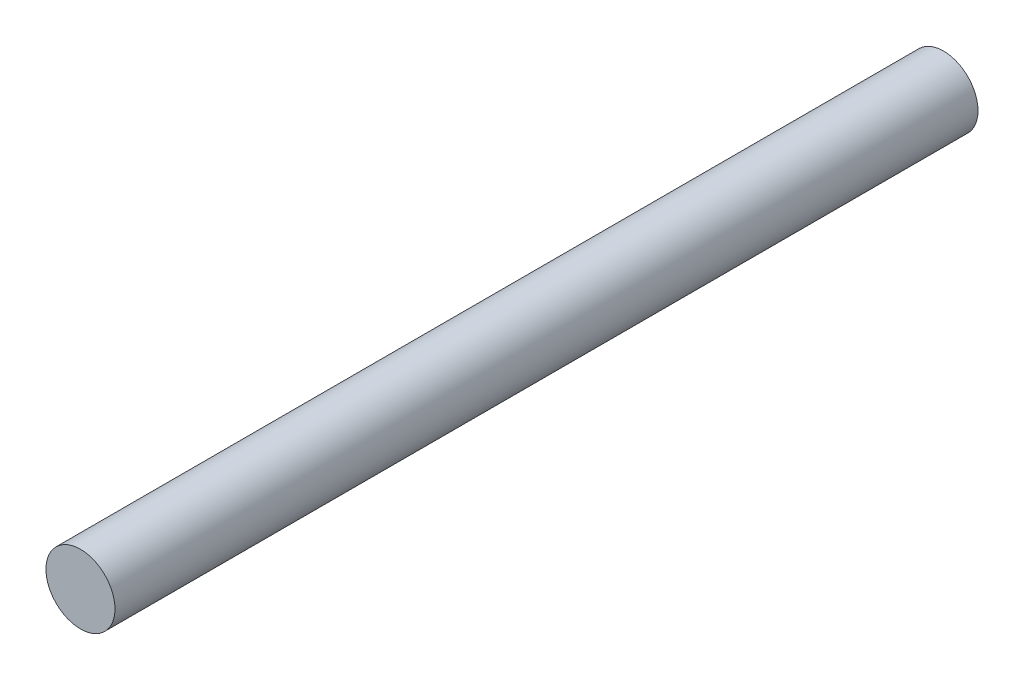
SolidWorks part; units mm, degrees
ref_plane "Front Plane" through (0, 0, 0) normal (0, 0, 1) x (1, 0, 0)
ref_plane "Top Plane" through (0, 0, 0) normal (0, 1, 0) x (1, 0, 0)
ref_plane "Right Plane" through (0, 0, 0) normal (1, 0, 0) x (0, 0, -1)
sketch "Sketch1" plane through (0, 0, 0) normal (0, 0, 1) x (1, 0, 0)
  circle A0 centre (0, 0) radius 3
  dimension "D1" = 6
extrude "Boss-Extrude1" add sketch "Sketch1" along normal blind 75
